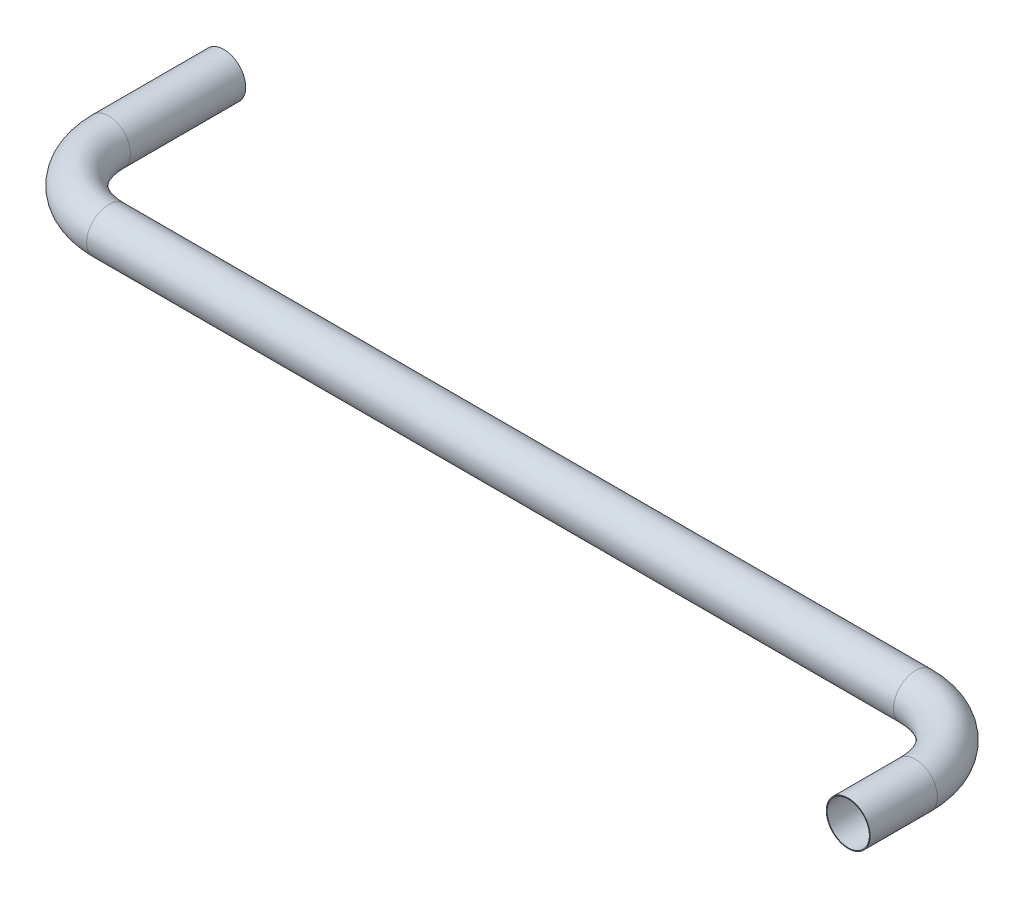
SolidWorks part; units mm, degrees
ref_plane "Front Plane" through (0, 0, 0) normal (0, 0, 1) x (1, 0, 0)
ref_plane "Top Plane" through (0, 0, 0) normal (0, 1, 0) x (1, 0, 0)
ref_plane "Right Plane" through (0, 0, 0) normal (1, 0, 0) x (0, 0, -1)
sketch "Sketch1" plane through (0, 0, 0) normal (0, 1, 0) x (1, 0, 0)
  line L0 (0, 0) -> (0, 140)
  line L1 (-160, 300) -> (-1840, 300)
  line L2 (-2000, 460) -> (-2000, 700)
  arc A0 (0, 140) -> (-160, 300) centre (-160, 140) ccw
  arc A1 (-1840, 300) -> (-2000, 460) centre (-1840, 460) cw
  point P7 (0, 300)
  point P10 (-2000, 300)
  dimension "D4" = 160
  dimension "D1" = 2000
  dimension "D2" = 300
  dimension "D3" = 400
sketch "Sketch2" plane through (0, 0, 0) normal (0, 0, 1) x (1, 0, 0)
  circle A0 centre (0, 0) radius 45.59
  circle A1 centre (0, 0) radius 44.09
  dimension "D1" = 88.18
  dimension "D2" = 91.18
sweep "Sweep1" add profiles "Sketch2" path "Sketch1"
